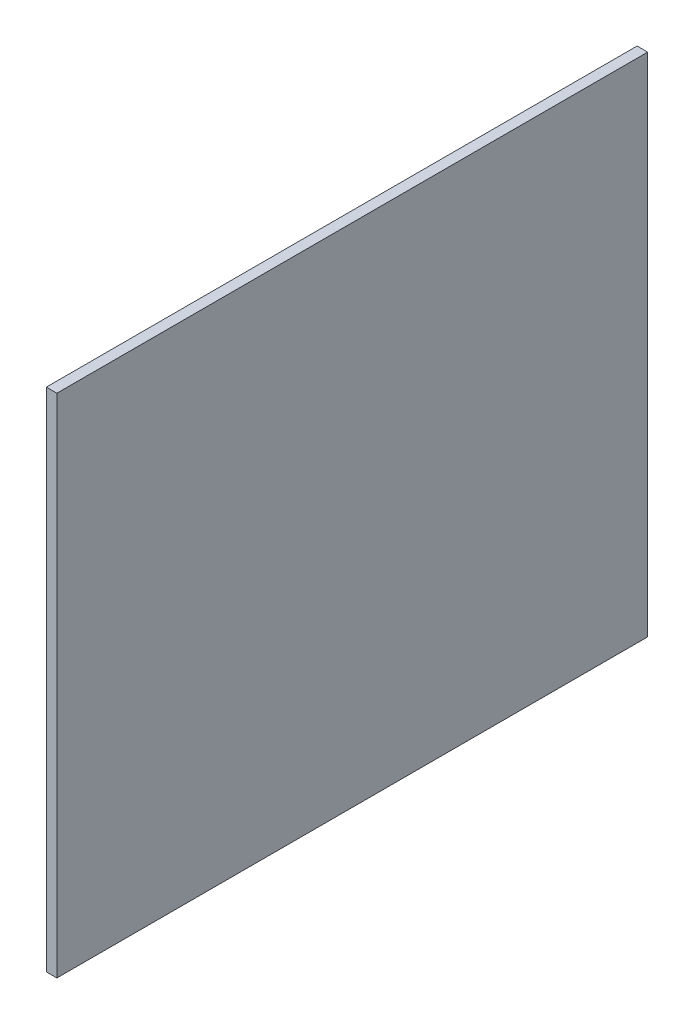
SolidWorks part; units mm, degrees
material "Custom Plastic"
ref_plane "X-Y Datum" through (0, 0, 0) normal (0, 0, 1) x (1, 0, 0)
ref_plane "X-Z Datum" through (0, 0, 0) normal (0, 1, 0) x (1, 0, 0)
ref_plane "Y-Z Datum" through (0, 0, 0) normal (1, 0, 0) x (0, 0, -1)
sketch "Sketch1" plane through (0, 0, 0) normal (0, 1, 0) x (1, 0, 0)
  line L1 (0, 0) -> (-12.7, 0)
  line L2 (0, 0) -> (0, -711.2)
  line L3 (0, -711.2) -> (-12.7, -711.2)
  line L4 (-12.7, 0) -> (-12.7, -711.2)
  dimension "D1" = 12.7
  dimension "D2" = 711.2
extrude "Boss-Extrude1" add sketch "Sketch1" against normal blind 609.6
